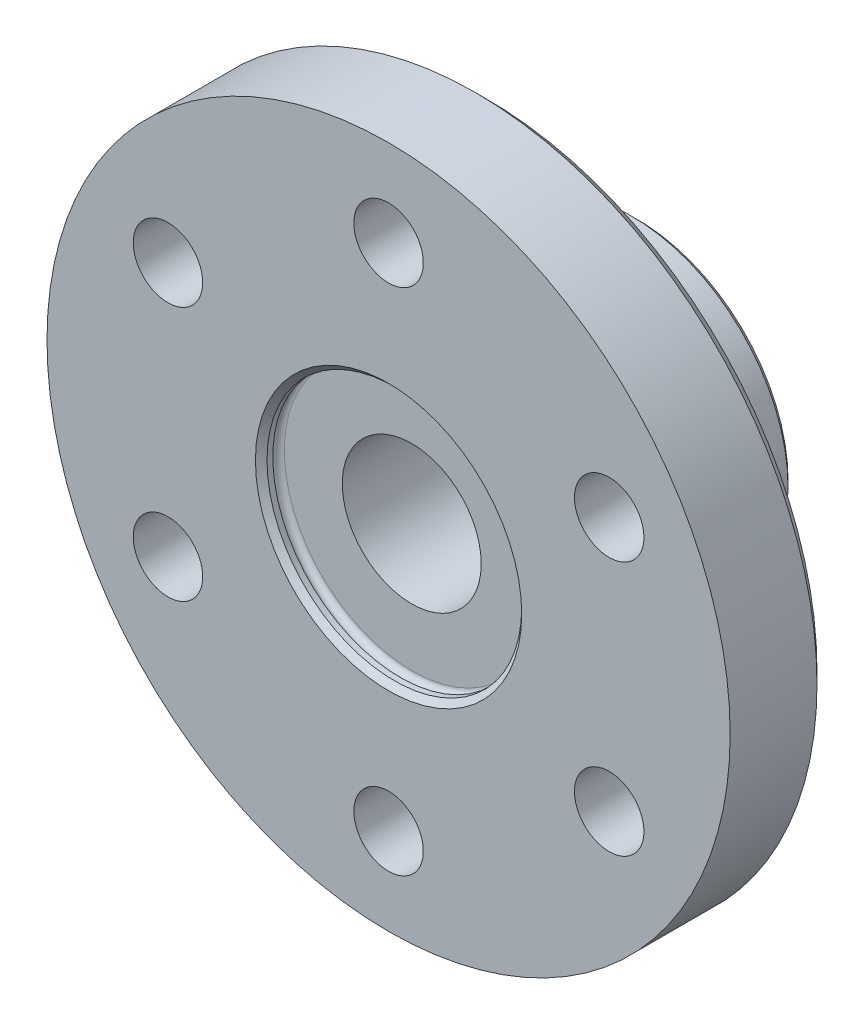
SolidWorks part; units mm, degrees
ref_plane "Front Plane" through (0, 0, 0) normal (0, 0, 1) x (1, 0, 0)
ref_plane "Top Plane" through (0, 0, 0) normal (0, 1, 0) x (1, 0, 0)
ref_plane "Right Plane" through (0, 0, 0) normal (1, 0, 0) x (0, 0, -1)
sketch "Sketch1" plane through (0, 0, 0) normal (1, 0, 0) x (0, 0, -1)
  line L0 (-9.0012, 0) -> (24.6865, 0) construction
  line L1 (1.3764, 12) -> (1.3764, 22)
  line L2 (-0.6236, 22) -> (-2.6236, 22)
  line L3 (-2.6236, 22) -> (-2.6236, 59)
  line L4 (-2.6236, 59) -> (14.3764, 59)
  line L5 (14.3764, 59) -> (14.3764, 27)
  line L6 (14.3764, 27) -> (40.3764, 27)
  line L7 (40.3764, 27) -> (40.3764, 12)
  line L9 (1.3764, 12) -> (40.3764, 12)
  arc A0 (1.3764, 22) -> (-0.6236, 22) centre (0.3764, 22) ccw
  dimension "D1" = 1
  dimension "D2" = 118
  dimension "D3" = 54
  dimension "D4" = 44
  dimension "D5" = 24
  dimension "D6" = 17
  dimension "D7" = 43
  dimension "D8" = 4
revolve "Revolve1" add sketch "Sketch1" angle 360 about L0
sketch "Sketch2" plane through (0, 0, -14.3764) normal (0, 0, -1) x (-1, 0, 0)
  circle A0 centre (0, 44) radius 6
  dimension "D1" = 12
  dimension "D2" = 44
extrude "Cut-Extrude1" cut sketch "Sketch2" against normal up to next
pattern_circular "CirPattern1" count 6 over 360 about axis through (0, 0, 0) along (0, 0, 1) of "Cut-Extrude1"
fillet "Fillet1" radius 2 1 edges at (27, 0, -14.3764)
chamfer "Chamfer1" distance 1 angle 45 3 edges at (22, 0, 2.6236) (12, 0, -40.3764) (27, 0, -40.3764)
chamfer "Chamfer2" distance 2 angle 45 1 edges at (59, 0, -14.3764)
